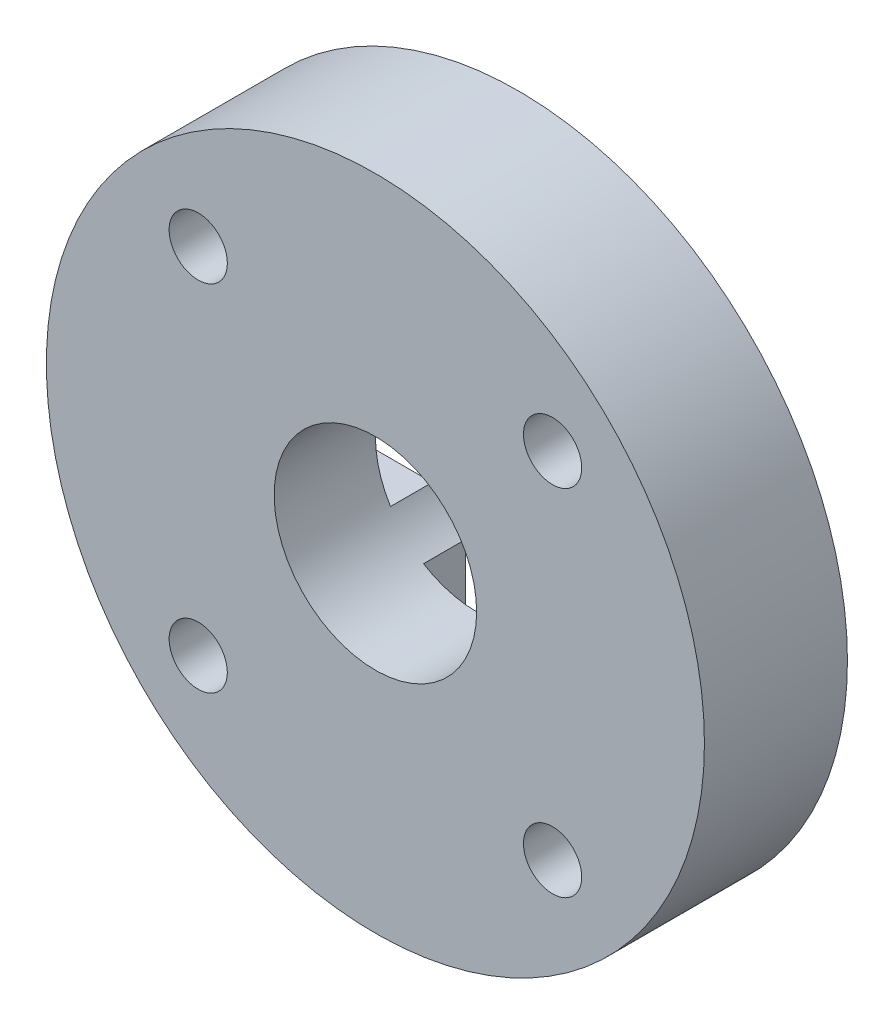
SolidWorks part; units mm, degrees
ref_plane "Front Plane" through (0, 0, 0) normal (0, 0, 1) x (1, 0, 0)
ref_plane "Top Plane" through (0, 0, 0) normal (0, 1, 0) x (1, 0, 0)
ref_plane "Right Plane" through (0, 0, 0) normal (1, 0, 0) x (0, 0, -1)
sketch "Trial_load_plate_profile" plane through (0, 0, 0) normal (0, 0, 1) x (1, 0, 0)
  circle A0 centre (0, 0) radius 13
  circle A1 centre (0, 0) radius 4
  dimension "D1" = 26
  dimension "D2" = 8
extrude "Trial_load_plate" add sketch "Trial_load_plate_profile" along normal blind 4
sketch "Captured_horn_key_boss_profile" plane through (0, 0, 0) normal (0, 0, 1) x (1, 0, 0)
  circle A0 centre (0, 0) radius 13
  dimension "D1" = 26
extrude "Captured_horn_key_boss" add sketch "Captured_horn_key_boss_profile" along normal blind 1.65 from offset 1.65
sketch "Stock_horn_pocket_Hub" plane through (0, 0, 0) normal (0, 0, 1) x (1, 0, 0)
  circle A0 centre (0, 0) radius 3.55
  dimension "D1" = 7.1
extrude "Key_pocket_Hub" cut sketch "Stock_horn_pocket_Hub" along normal blind 1.65 from offset 1.65
sketch "Stock_horn_pocket_Horizontal" plane through (0, 0, 0) normal (0, 0, 1) x (1, 0, 0)
  line L1 (-8.15, -2.1) -> (8.15, -2.1)
  line L2 (-8.15, -2.1) -> (-8.15, 2.1)
  line L3 (-8.15, 2.1) -> (8.15, 2.1)
  line L4 (8.15, -2.1) -> (8.15, 2.1)
  dimension "D1" = 16.3
  dimension "D2" = 4.2
extrude "Key_pocket_Horizontal" cut sketch "Stock_horn_pocket_Horizontal" along normal blind 1.65 from offset 1.65
sketch "Stock_horn_pocket_Vertical" plane through (0, 0, 0) normal (0, 0, 1) x (1, 0, 0)
  line L1 (-2.1, -8.15) -> (2.1, -8.15)
  line L2 (-2.1, -8.15) -> (-2.1, 8.15)
  line L3 (-2.1, 8.15) -> (2.1, 8.15)
  line L4 (2.1, -8.15) -> (2.1, 8.15)
  dimension "D1" = 4.2
  dimension "D2" = 16.3
extrude "Key_pocket_Vertical" cut sketch "Stock_horn_pocket_Vertical" along normal blind 1.65 from offset 1.65
sketch "Stock_horn_pocket_Rounded_tips" plane through (0, 0, 0) normal (0, 0, 1) x (1, 0, 0)
  circle A0 centre (8.15, 0) radius 2.1
  circle A1 centre (-8.15, 0) radius 2.1
  circle A2 centre (0, 8.15) radius 2.1
  circle A3 centre (0, -8.15) radius 2.1
  dimension "D1" = 4.2
  dimension "D2" = 4.2
  dimension "D3" = 4.2
  dimension "D4" = 4.2
extrude "Key_pocket_Rounded_tips" cut sketch "Stock_horn_pocket_Rounded_tips" along normal blind 1.65 from offset 1.65
sketch "Unmodified_horn_capture_M2_profile" plane through (0, 0, 0) normal (0, 0, 1) x (1, 0, 0)
  circle A0 centre (7, 7) radius 1.15
  circle A1 centre (-7, 7) radius 1.15
  circle A2 centre (-7, -7) radius 1.15
  circle A3 centre (7, -7) radius 1.15
  dimension "D1" = 2.3
  dimension "D2" = 2.3
  dimension "D3" = 2.3
  dimension "D4" = 2.3
extrude "Unmodified_horn_capture_M2" cut sketch "Unmodified_horn_capture_M2_profile" along normal through all from offset 50
sketch "Horn_center_hub_clearance" plane through (0, 0, 0) normal (0, 0, 1) x (1, 0, 0)
  circle A0 centre (0, 0) radius 4
  dimension "D1" = 8
extrude "Hub_clearance_in_key_boss_only" cut sketch "Horn_center_hub_clearance" along normal blind 1.65 from offset 1.65
